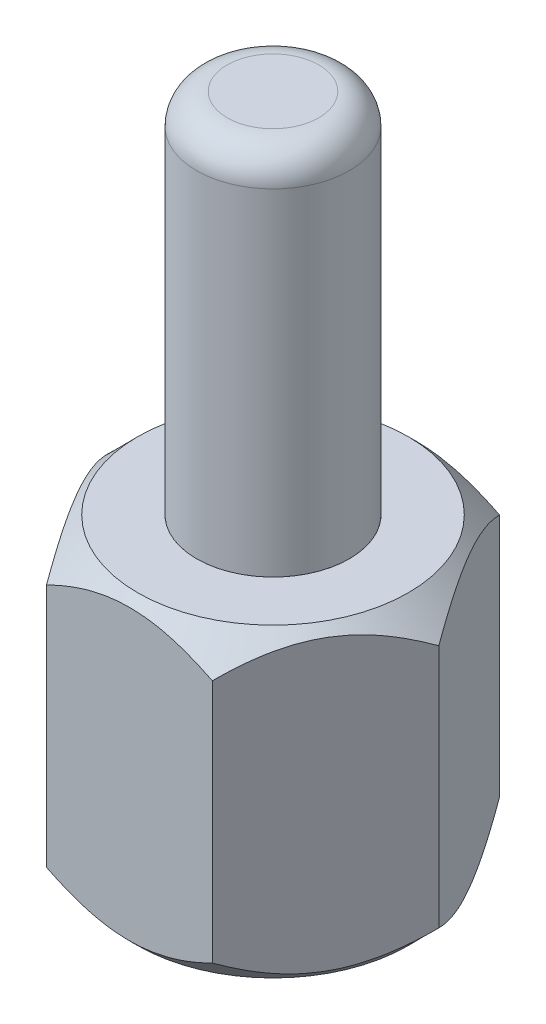
SolidWorks part; units mm, degrees
ref_plane "前视基准面" through (0, 0, 0) normal (0, 0, 1) x (1, 0, 0)
ref_plane "上视基准面" through (0, 0, 0) normal (0, 1, 0) x (1, 0, 0)
ref_plane "右视基准面" through (0, 0, 0) normal (1, 0, 0) x (0, 0, -1)
other "Configuration Table"
sketch "草图1" plane through (0, 0, 0) normal (0, 1, 0) x (1, 0, 0)
  line L1 (2.7135, 0) -> (1.3568, 2.35)
  line L2 (1.3568, 2.35) -> (-1.3568, 2.35)
  line L3 (-1.3568, 2.35) -> (-2.7135, 0)
  line L4 (-2.7135, 0) -> (-1.3568, -2.35)
  line L5 (-1.3568, -2.35) -> (1.3568, -2.35)
  line L6 (1.3568, -2.35) -> (2.7135, 0)
  circle A0 centre (0, 0) radius 2.35 construction
  dimension "D1" = 4.7
extrude "凸台-拉伸1" add sketch "草图1" along normal blind 5
sketch "草图2" plane through (0, 0, 0) normal (0, -1, 0) x (1, 0, 0)
  circle A0 centre (0, 0) radius 1.25
  dimension "D1" = 2.5
extrude "切除-拉伸1" cut sketch "草图2" against normal blind 10
sketch "草图4" plane through (0, 5, 0) normal (0, 1, 0) x (1, 0, 0)
  line L6 (1.3568, -2.35) -> (2.7135, 0)
  line L7 (2.7135, 0) -> (1.3568, 2.35)
  line L8 (1.3568, 2.35) -> (-1.3568, 2.35)
  line L9 (-1.3568, 2.35) -> (-2.7135, 0)
  line L10 (-2.7135, 0) -> (-1.3568, -2.35)
  line L11 (-1.3568, -2.35) -> (1.3568, -2.35)
  line L12 (1.3568, -2.35) -> (2.7135, 0)
  line L13 (2.7135, 0) -> (1.3568, 2.35)
  line L14 (1.3568, 2.35) -> (-1.3568, 2.35)
  line L15 (-1.3568, 2.35) -> (-2.7135, 0)
  line L16 (-2.7135, 0) -> (-1.3568, -2.35)
  line L17 (-1.3568, -2.35) -> (1.3568, -2.35)
  circle A1 centre (0, 0) radius 1.25
  circle A2 centre (0, 0) radius 1.25
  dimension "D1" = 0
  dimension "D2" = 0
extrude "凸台-拉伸2" add sketch "草图4" along normal blind 6 separate body contours A2
fillet "圆角1" radius 0.5 1 edges at (0, 11, 1.25)
sketch "草图7" plane through (0, 0, 0) normal (0, 0, 1) x (1, 0, 0)
  line L0 (-2.7135, 5) -> (-2.7135, 4.5)
  line L1 (-2.7135, 5) -> (-2.7135, 0) construction
  line L2 (-2.7135, 4.5) -> (-2.2135, 5)
  line L3 (-2.7135, 5) -> (-1.3568, 5) construction
  line L4 (-2.2135, 5) -> (-2.7135, 5)
  line L5 (0, 0) -> (1.4452, 0.3873)
  line L6 (0, 0) -> (0, 8.786) construction
  dimension "D1" = 0.5
  dimension "D2" = 0.5
revolve "切除-旋转4" cut sketch "草图7" angle 360 about L6
ref_plane "基准面1" through (0, 2.5, 0) normal (0, -1, 0) x (-1, 0, 0)
mirror "镜向1" about plane through (0, 2.5, 0) normal (0, -1, 0) of "切除-旋转4"
